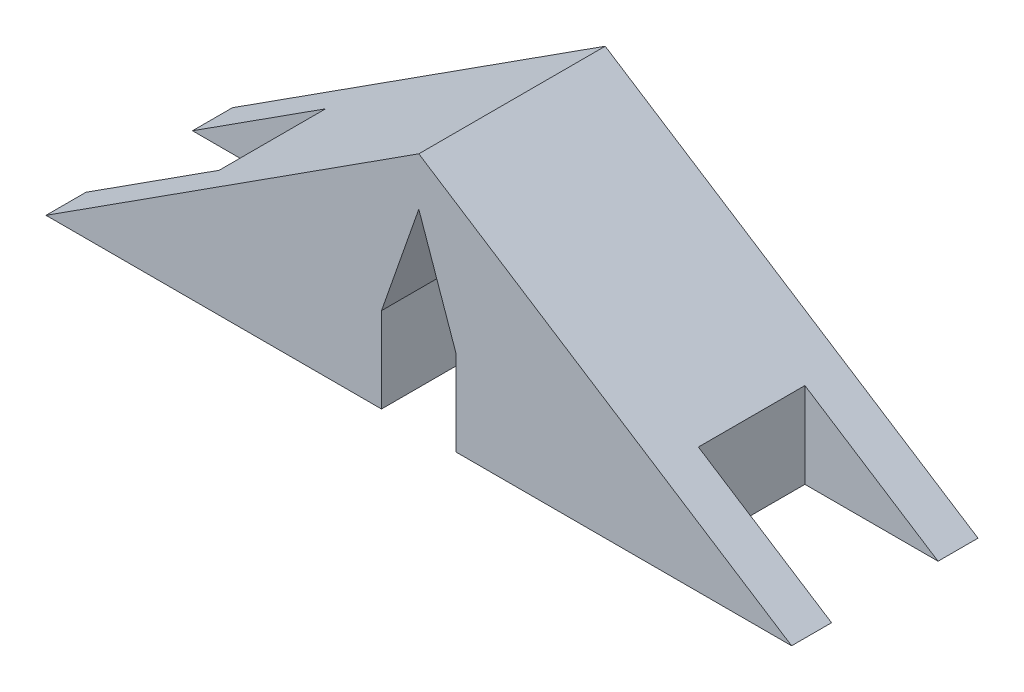
SolidWorks part; units mm, degrees
ref_plane "Спереди" through (0, 0, 0) normal (0, 0, 1) x (1, 0, 0)
ref_plane "Сверху" through (0, 0, 0) normal (0, 1, 0) x (1, 0, 0)
ref_plane "Справа" through (0, 0, 0) normal (1, 0, 0) x (0, 0, -1)
sketch "Эскиз1" plane through (0, 0, 0) normal (0, 0, 1) x (1, 0, 0)
  line L0 (-35, -22.5) -> (35, 22.5)
  line L1 (-35, -22.5) -> (35, -22.5)
  line L2 (-35, -22.5) -> (-35, 22.5)
  line L3 (-35, 22.5) -> (35, 22.5)
  line L4 (35, -22.5) -> (35, 22.5)
  line L5 (-35, -22.5) -> (35, 22.5) construction
  line L6 (-35, 22.5) -> (35, -22.5) construction
  line L7 (28, -22.5) -> (28, -6.5)
  line L8 (28, -6.5) -> (35, 13.5)
  point P0 (0, 0)
  dimension "D1" = 45
  dimension "D2" = 70
  dimension "D3" = 7
  dimension "D4" = 16
  dimension "D5" = 36
extrude "Бобышка-Вытянуть1" add sketch "Эскиз1" along normal blind 35 contours L7 L8 L4 L0 L1
sketch "Эскиз2" plane through (0, -22.5, 0) normal (0, -1, 0) x (1, 0, 0)
  line L0 (-35, 17.5) -> (35, 17.5) construction
  line L1 (-35, 35) -> (-35, 0) construction
  line L2 (35, 35) -> (35, 0) construction
  line L4 (-10, 7.5) -> (-35, 7.5)
  line L5 (-10, 7.5) -> (-10, 27.5)
  line L6 (-10, 27.5) -> (-35, 27.5)
  line L7 (-35, 7.5) -> (-35, 27.5)
  line L8 (-10, 7.5) -> (-35, 27.5) construction
  line L9 (-10, 27.5) -> (-35, 7.5) construction
  point P6 (-22.5, 17.5)
  dimension "D1" = 25
  dimension "D2" = 20
extrude "Вырез-Вытянуть1" cut sketch "Эскиз2" against normal through all
mirror "Зеркальное отражение1" about plane through (35, 0, 35) normal (-1, 0, 0) of "Вырез-Вытянуть1", "Бобышка-Вытянуть1"
